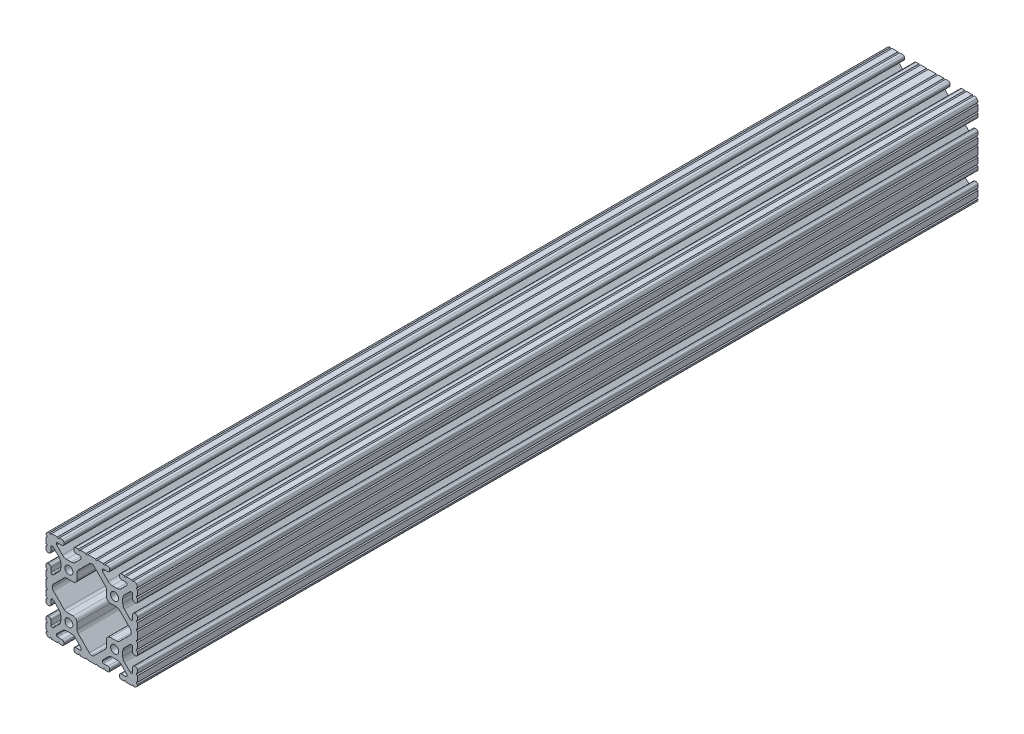
SolidWorks part; units mm, degrees
ref_plane "Front Plane" through (0, 0, 0) normal (0, 0, 1) x (1, 0, 0)
ref_plane "Top Plane" through (0, 0, 0) normal (0, 1, 0) x (1, 0, 0)
ref_plane "Right Plane" through (0, 0, 0) normal (1, 0, 0) x (0, 0, -1)
sketch "Sketch1" plane through (0, 0, 0) normal (0, 0, 1) x (1, 0, 0)
  line L0 (0, 38.1) -> (0, -38.1) construction
  line L1 (-38.1, -38.1) -> (38.1, -38.1) construction
  line L2 (-38.1, -38.1) -> (-38.1, 38.1) construction
  line L3 (-38.1, 38.1) -> (38.1, 38.1) construction
  line L4 (38.1, -38.1) -> (38.1, 38.1) construction
  line L5 (0, 38.1) -> (0, -38.1) construction
  line L6 (-38.1, 0) -> (38.1, 0) construction
  line L7 (-19.05, 19.05) -> (19.05, 19.05) construction
  line L8 (-19.05, 19.05) -> (-19.05, -19.05) construction
  line L9 (-19.05, -19.05) -> (19.05, -19.05) construction
  line L10 (19.05, 19.05) -> (19.05, -19.05) construction
  line L11 (-23.114, 38.1) -> (-23.114, -38.1) construction
  line L12 (-23.114, -38.1) -> (-14.986, 38.1) construction
  line L13 (-14.986, 38.1) -> (-14.986, -38.1) construction
  circle A0 centre (19.05, 19.05) radius 3.3274
  point P0 (0, 0)
  point P9 (0, 0)
  point P12 (-19.05, 0)
  line B0 (-11.3637, -22.8433) -> (-2.0515, -32.1555)
  line B1 (-12.2936, -15.4686) -> (-12.2936, -20.5983)
  line B2 (-20.769, -12.2936) -> (-15.4686, -12.2936)
  line B3 (-31.9021, -2.4756) -> (-23.0141, -11.3637)
  line B4 (-23.0141, 11.3637) -> (-31.9021, 2.4756)
  line B5 (-15.4686, 12.2936) -> (-20.769, 12.2936)
  line B6 (-12.2936, 20.5983) -> (-12.2936, 15.4686)
  line B7 (-2.0515, 32.1555) -> (-11.3637, 22.8433)
  line B8 (11.3637, 22.8433) -> (2.0515, 32.1555)
  line B9 (12.2936, 15.4686) -> (12.2936, 20.5983)
  line B10 (20.769, 12.2936) -> (15.4686, 12.2936)
  line B11 (31.9021, 2.4756) -> (23.0141, 11.3637)
  line B12 (23.0141, -11.3637) -> (31.9021, -2.4756)
  line B13 (15.4686, -12.2936) -> (20.769, -12.2936)
  line B14 (12.2936, -20.5983) -> (12.2936, -15.4686)
  line B15 (2.0515, -32.1555) -> (11.3637, -22.8433)
  line B16 (-4.7773, 38.1) -> (-9.6053, 38.1)
  line B17 (-11.1289, 38.1) -> (-13.4112, 38.1)
  line B18 (-14.986, 36.5252) -> (-14.986, 35.6108)
  line B19 (-13.4112, 34.036) -> (-9.652, 34.036)
  line B20 (-8.763, 33.147) -> (-8.763, 32.4935)
  line B21 (-9.0234, 31.8649) -> (-13.6907, 27.1976)
  line B22 (-17.0493, 25.8064) -> (-21.0507, 25.8064)
  line B23 (-24.4093, 27.1976) -> (-29.1002, 31.8885)
  line B24 (-29.337, 32.7207) -> (-29.337, 33.147)
  line B25 (-28.448, 34.036) -> (-24.6888, 34.036)
  line B26 (-23.114, 35.6108) -> (-23.114, 36.5252)
  line B27 (-24.6888, 38.1) -> (-27.0772, 38.1)
  line B28 (-28.6011, 38.1) -> (-33.4288, 38.1)
  line B29 (-38.1, 33.373) -> (-38.1, 28.5453)
  line B30 (-38.1, 27.0238) -> (-38.1, 24.6302)
  line B31 (-36.5252, 23.0554) -> (-35.6108, 23.0554)
  line B32 (-34.036, 24.6302) -> (-34.036, 28.448)
  line B33 (-33.147, 29.337) -> (-32.6643, 29.337)
  line B34 (-32.0357, 29.0766) -> (-27.1976, 24.2385)
  line B35 (-25.8064, 20.8799) -> (-25.8064, 17.2201)
  line B36 (-27.1976, 13.8615) -> (-31.9489, 9.1101)
  line B37 (-32.7869, 8.763) -> (-33.0603, 8.763)
  line B38 (-34.036, 9.7387) -> (-34.036, 13.4698)
  line B39 (-35.6108, 15.0446) -> (-36.5252, 15.0446)
  line B40 (-38.1, 13.4698) -> (-38.1, 11.075)
  line B41 (-38.1, 9.552) -> (-38.1, 4.7238)
  line B42 (-38.1, 3.2007) -> (-38.1, -3.2007)
  line B43 (-38.1, -4.7238) -> (-38.1, -9.552)
  line B44 (-38.1, -11.075) -> (-38.1, -13.4698)
  line B45 (-36.5252, -15.0446) -> (-35.6108, -15.0446)
  line B46 (-34.036, -13.4698) -> (-34.036, -9.7387)
  line B47 (-33.0603, -8.763) -> (-32.7869, -8.763)
  line B48 (-31.9489, -9.1101) -> (-27.1976, -13.8615)
  line B49 (-25.8064, -17.2201) -> (-25.8064, -20.8799)
  line B50 (-27.1976, -24.2385) -> (-32.0357, -29.0766)
  line B51 (-32.6643, -29.337) -> (-33.147, -29.337)
  line B52 (-34.036, -28.448) -> (-34.036, -24.6302)
  line B53 (-35.6108, -23.0554) -> (-36.5252, -23.0554)
  line B54 (-38.1, -24.6302) -> (-38.1, -27.0238)
  line B55 (-38.1, -28.5453) -> (-38.1, -33.373)
  line B56 (-33.4288, -38.1) -> (-28.6011, -38.1)
  line B57 (-27.0772, -38.1) -> (-24.6888, -38.1)
  line B58 (-23.114, -36.5252) -> (-23.114, -35.6108)
  line B59 (-24.6888, -34.036) -> (-28.448, -34.036)
  line B60 (-29.337, -33.147) -> (-29.337, -32.7207)
  line B61 (-29.1002, -31.8885) -> (-24.4093, -27.1976)
  line B62 (-21.0507, -25.8064) -> (-17.0493, -25.8064)
  line B63 (-13.6907, -27.1976) -> (-9.0234, -31.8649)
  line B64 (-8.763, -32.4935) -> (-8.763, -33.147)
  line B65 (-9.652, -34.036) -> (-13.4112, -34.036)
  line B66 (-14.986, -35.6108) -> (-14.986, -36.5252)
  line B67 (-13.4112, -38.1) -> (-11.1289, -38.1)
  line B68 (-9.6053, -38.1) -> (-4.7773, -38.1)
  line B69 (-3.2537, -38.1) -> (3.2537, -38.1)
  line B70 (4.7773, -38.1) -> (9.6053, -38.1)
  line B71 (11.1289, -38.1) -> (13.4112, -38.1)
  line B72 (14.986, -36.5252) -> (14.986, -35.6108)
  line B73 (13.4112, -34.036) -> (9.652, -34.036)
  line B74 (8.763, -33.147) -> (8.763, -32.4935)
  line B75 (9.0234, -31.8649) -> (13.6907, -27.1976)
  line B76 (17.0493, -25.8064) -> (21.0507, -25.8064)
  line B77 (24.4093, -27.1976) -> (29.1002, -31.8885)
  line B78 (29.337, -32.7207) -> (29.337, -33.147)
  line B79 (28.448, -34.036) -> (24.6888, -34.036)
  line B80 (23.114, -35.6108) -> (23.114, -36.5252)
  line B81 (24.6888, -38.1) -> (27.0772, -38.1)
  line B82 (28.6011, -38.1) -> (33.4288, -38.1)
  line B83 (38.1, -33.373) -> (38.1, -28.5453)
  line B84 (38.1, -27.0238) -> (38.1, -24.6302)
  line B85 (36.5252, -23.0554) -> (35.6108, -23.0554)
  line B86 (34.036, -24.6302) -> (34.036, -28.448)
  line B87 (33.147, -29.337) -> (32.6643, -29.337)
  line B88 (32.0357, -29.0766) -> (27.1976, -24.2385)
  line B89 (25.8064, -20.8799) -> (25.8064, -17.2201)
  line B90 (27.1976, -13.8615) -> (31.9489, -9.1101)
  line B91 (32.7869, -8.763) -> (33.0603, -8.763)
  line B92 (34.036, -9.7387) -> (34.036, -13.4698)
  line B93 (35.6108, -15.0446) -> (36.5252, -15.0446)
  line B94 (38.1, -13.4698) -> (38.1, -11.075)
  line B95 (38.1, -9.552) -> (38.1, -4.7238)
  line B96 (38.1, -3.2007) -> (38.1, 3.2007)
  line B97 (38.1, 4.7238) -> (38.1, 9.552)
  line B98 (38.1, 11.075) -> (38.1, 13.4698)
  line B99 (36.5252, 15.0446) -> (35.6108, 15.0446)
  line B100 (34.036, 13.4698) -> (34.036, 9.7387)
  line B101 (33.0603, 8.763) -> (32.7869, 8.763)
  line B102 (31.9489, 9.1101) -> (27.1976, 13.8615)
  line B103 (25.8064, 17.2201) -> (25.8064, 20.8799)
  line B104 (27.1976, 24.2385) -> (32.0357, 29.0766)
  line B105 (32.6643, 29.337) -> (33.147, 29.337)
  line B106 (34.036, 28.448) -> (34.036, 24.6302)
  line B107 (35.6108, 23.0554) -> (36.5252, 23.0554)
  line B108 (38.1, 24.6302) -> (38.1, 27.0238)
  line B109 (38.1, 28.5453) -> (38.1, 33.373)
  line B110 (33.4288, 38.1) -> (28.6011, 38.1)
  line B111 (27.0772, 38.1) -> (24.6888, 38.1)
  line B112 (23.114, 36.5252) -> (23.114, 35.6108)
  line B113 (24.6888, 34.036) -> (28.448, 34.036)
  line B114 (29.337, 33.147) -> (29.337, 32.7207)
  line B115 (29.1002, 31.8885) -> (24.4093, 27.1976)
  line B116 (21.0507, 25.8064) -> (17.0493, 25.8064)
  line B117 (13.6907, 27.1976) -> (9.0234, 31.8649)
  line B118 (8.763, 32.4935) -> (8.763, 33.147)
  line B119 (9.652, 34.036) -> (13.4112, 34.036)
  line B120 (14.986, 35.6108) -> (14.986, 36.5252)
  line B121 (13.4112, 38.1) -> (11.1289, 38.1)
  line B122 (9.6053, 38.1) -> (4.7773, 38.1)
  line B123 (3.2537, 38.1) -> (-3.2537, 38.1)
  circle B124 centre (-19.05, 19.05) radius 3.3274
  circle B125 centre (-19.05, -19.05) radius 3.3274
  circle B126 centre (19.05, -19.05) radius 3.3274
  circle B127 centre (19.05, 19.05) radius 3.3274
  arc B128 (0, -33.011) -> (2.0515, -32.1555) centre (-0.0139, -30.09) ccw
  arc B129 (-2.0515, -32.1555) -> (0, -33.011) centre (0.0139, -30.09) ccw
  arc B130 (-12.2936, -20.5983) -> (-11.3637, -22.8433) centre (-9.1186, -20.5983) ccw
  arc B131 (-12.2936, -15.4686) -> (-15.4686, -12.2936) centre (-15.4686, -15.4686) ccw
  arc B132 (-23.0141, -11.3637) -> (-20.769, -12.2936) centre (-20.769, -9.1186) ccw
  arc B133 (-32.7287, 0) -> (-31.9021, -2.4756) centre (-29.8367, -0.4102) ccw
  arc B134 (-31.9021, 2.4756) -> (-32.7287, 0) centre (-29.8367, 0.4102) ccw
  arc B135 (-20.769, 12.2936) -> (-23.0141, 11.3637) centre (-20.769, 9.1186) ccw
  arc B136 (-15.4686, 12.2936) -> (-12.2936, 15.4686) centre (-15.4686, 15.4686) ccw
  arc B137 (-11.3637, 22.8433) -> (-12.2936, 20.5983) centre (-9.1186, 20.5983) ccw
  arc B138 (0, 33.011) -> (-2.0515, 32.1555) centre (0.0139, 30.09) ccw
  arc B139 (2.0515, 32.1555) -> (0, 33.011) centre (-0.0139, 30.09) ccw
  arc B140 (12.2936, 20.5983) -> (11.3637, 22.8433) centre (9.1186, 20.5983) ccw
  arc B141 (12.2936, 15.4686) -> (15.4686, 12.2936) centre (15.4686, 15.4686) ccw
  arc B142 (23.0141, 11.3637) -> (20.769, 12.2936) centre (20.769, 9.1186) ccw
  arc B143 (32.7287, 0) -> (31.9021, 2.4756) centre (29.8367, 0.4102) ccw
  arc B144 (31.9021, -2.4756) -> (32.7287, 0) centre (29.8367, -0.4102) ccw
  arc B145 (20.769, -12.2936) -> (23.0141, -11.3637) centre (20.769, -9.1186) ccw
  arc B146 (15.4686, -12.2936) -> (12.2936, -15.4686) centre (15.4686, -15.4686) ccw
  arc B147 (11.3637, -22.8433) -> (12.2936, -20.5983) centre (9.1186, -20.5983) ccw
  arc B148 (-4.7773, 38.1) -> (-3.2537, 38.1) centre (-4.0155, 38.0824) ccw
  arc B149 (-11.1289, 38.1) -> (-9.6053, 38.1) centre (-10.3671, 38.0824) ccw
  arc B150 (-13.4112, 38.1) -> (-14.986, 36.5252) centre (-13.4112, 36.5252) ccw
  arc B151 (-14.986, 35.6108) -> (-13.4112, 34.036) centre (-13.4112, 35.6108) ccw
  arc B152 (-8.763, 33.147) -> (-9.652, 34.036) centre (-9.652, 33.147) ccw
  arc B153 (-9.0234, 31.8649) -> (-8.763, 32.4935) centre (-9.652, 32.4935) ccw
  arc B154 (-17.0493, 25.8064) -> (-13.6907, 27.1976) centre (-17.0493, 30.5562) ccw
  arc B155 (-24.4093, 27.1976) -> (-21.0507, 25.8064) centre (-21.0507, 30.5562) ccw
  arc B156 (-29.337, 32.7207) -> (-29.1002, 31.8885) centre (-28.4716, 32.5172) ccw
  arc B157 (-28.448, 34.036) -> (-29.337, 33.147) centre (-28.448, 33.147) ccw
  arc B158 (-24.6888, 34.036) -> (-23.114, 35.6108) centre (-24.6888, 35.6108) ccw
  arc B159 (-23.114, 36.5252) -> (-24.6888, 38.1) centre (-24.6888, 36.5252) ccw
  arc B160 (-28.6011, 38.1) -> (-27.0772, 38.1) centre (-27.8392, 38.0824) ccw
  arc B161 (-34.9527, 38.1) -> (-33.4288, 38.1) centre (-34.1907, 38.0824) ccw
  arc B162 (-34.9527, 38.1) -> (-37.0861, 37.1826) centre (-34.8521, 34.9266) ccw
  arc B163 (-37.0861, 37.1826) -> (-38.1, 34.8455) centre (-34.925, 34.8566) ccw
  arc B164 (-38.1, 33.373) -> (-38.1, 34.8455) centre (-37.9035, 34.1092) ccw
  arc B165 (-38.1, 27.0238) -> (-38.1, 28.5453) centre (-37.9035, 27.7845) ccw
  arc B166 (-38.1, 24.6302) -> (-36.5252, 23.0554) centre (-36.5252, 24.6302) ccw
  arc B167 (-35.6108, 23.0554) -> (-34.036, 24.6302) centre (-35.6108, 24.6302) ccw
  arc B168 (-33.147, 29.337) -> (-34.036, 28.448) centre (-33.147, 28.448) ccw
  arc B169 (-32.0357, 29.0766) -> (-32.6643, 29.337) centre (-32.6643, 28.448) ccw
  arc B170 (-25.8064, 20.8799) -> (-27.1976, 24.2385) centre (-30.5562, 20.8799) ccw
  arc B171 (-27.1976, 13.8615) -> (-25.8064, 17.2201) centre (-30.5562, 17.2201) ccw
  arc B172 (-32.7869, 8.763) -> (-31.9489, 9.1101) centre (-32.7869, 9.9481) ccw
  arc B173 (-34.036, 9.7387) -> (-33.0603, 8.763) centre (-33.0603, 9.7387) ccw
  arc B174 (-34.036, 13.4698) -> (-35.6108, 15.0446) centre (-35.6108, 13.4698) ccw
  arc B175 (-36.5252, 15.0446) -> (-38.1, 13.4698) centre (-36.5252, 13.4698) ccw
  arc B176 (-38.1, 9.552) -> (-38.1, 11.075) centre (-37.9035, 10.3135) ccw
  arc B177 (-38.1, 3.2007) -> (-38.1, 4.7238) centre (-37.9035, 3.9622) ccw
  arc B178 (-38.1, -4.7238) -> (-38.1, -3.2007) centre (-37.9035, -3.9622) ccw
  arc B179 (-38.1, -11.075) -> (-38.1, -9.552) centre (-37.9035, -10.3135) ccw
  arc B180 (-38.1, -13.4698) -> (-36.5252, -15.0446) centre (-36.5252, -13.4698) ccw
  arc B181 (-35.6108, -15.0446) -> (-34.036, -13.4698) centre (-35.6108, -13.4698) ccw
  arc B182 (-33.0603, -8.763) -> (-34.036, -9.7387) centre (-33.0603, -9.7387) ccw
  arc B183 (-31.9489, -9.1101) -> (-32.7869, -8.763) centre (-32.7869, -9.9481) ccw
  arc B184 (-25.8064, -17.2201) -> (-27.1976, -13.8615) centre (-30.5562, -17.2201) ccw
  arc B185 (-27.1976, -24.2385) -> (-25.8064, -20.8799) centre (-30.5562, -20.8799) ccw
  arc B186 (-32.6643, -29.337) -> (-32.0357, -29.0766) centre (-32.6643, -28.448) ccw
  arc B187 (-34.036, -28.448) -> (-33.147, -29.337) centre (-33.147, -28.448) ccw
  arc B188 (-34.036, -24.6302) -> (-35.6108, -23.0554) centre (-35.6108, -24.6302) ccw
  arc B189 (-36.5252, -23.0554) -> (-38.1, -24.6302) centre (-36.5252, -24.6302) ccw
  arc B190 (-38.1, -28.5453) -> (-38.1, -27.0238) centre (-37.9035, -27.7845) ccw
  arc B191 (-38.1, -34.8455) -> (-38.1, -33.373) centre (-37.9035, -34.1092) ccw
  arc B192 (-38.1, -34.8455) -> (-37.0861, -37.1826) centre (-34.925, -34.8566) ccw
  arc B193 (-37.0861, -37.1826) -> (-34.9527, -38.1) centre (-34.8521, -34.9266) ccw
  arc B194 (-33.4288, -38.1) -> (-34.9527, -38.1) centre (-34.1907, -38.0824) ccw
  arc B195 (-27.0772, -38.1) -> (-28.6011, -38.1) centre (-27.8392, -38.0824) ccw
  arc B196 (-24.6888, -38.1) -> (-23.114, -36.5252) centre (-24.6888, -36.5252) ccw
  arc B197 (-23.114, -35.6108) -> (-24.6888, -34.036) centre (-24.6888, -35.6108) ccw
  arc B198 (-29.337, -33.147) -> (-28.448, -34.036) centre (-28.448, -33.147) ccw
  arc B199 (-29.1002, -31.8885) -> (-29.337, -32.7207) centre (-28.4716, -32.5172) ccw
  arc B200 (-21.0507, -25.8064) -> (-24.4093, -27.1976) centre (-21.0507, -30.5562) ccw
  arc B201 (-13.6907, -27.1976) -> (-17.0493, -25.8064) centre (-17.0493, -30.5562) ccw
  arc B202 (-8.763, -32.4935) -> (-9.0234, -31.8649) centre (-9.652, -32.4935) ccw
  arc B203 (-9.652, -34.036) -> (-8.763, -33.147) centre (-9.652, -33.147) ccw
  arc B204 (-13.4112, -34.036) -> (-14.986, -35.6108) centre (-13.4112, -35.6108) ccw
  arc B205 (-14.986, -36.5252) -> (-13.4112, -38.1) centre (-13.4112, -36.5252) ccw
  arc B206 (-9.6053, -38.1) -> (-11.1289, -38.1) centre (-10.3671, -38.0824) ccw
  arc B207 (-3.2537, -38.1) -> (-4.7773, -38.1) centre (-4.0155, -38.0824) ccw
  arc B208 (4.7773, -38.1) -> (3.2537, -38.1) centre (4.0155, -38.0824) ccw
  arc B209 (11.1289, -38.1) -> (9.6053, -38.1) centre (10.3671, -38.0824) ccw
  arc B210 (13.4112, -38.1) -> (14.986, -36.5252) centre (13.4112, -36.5252) ccw
  arc B211 (14.986, -35.6108) -> (13.4112, -34.036) centre (13.4112, -35.6108) ccw
  arc B212 (8.763, -33.147) -> (9.652, -34.036) centre (9.652, -33.147) ccw
  arc B213 (9.0234, -31.8649) -> (8.763, -32.4935) centre (9.652, -32.4935) ccw
  arc B214 (17.0493, -25.8064) -> (13.6907, -27.1976) centre (17.0493, -30.5562) ccw
  arc B215 (24.4093, -27.1976) -> (21.0507, -25.8064) centre (21.0507, -30.5562) ccw
  arc B216 (29.337, -32.7207) -> (29.1002, -31.8885) centre (28.4716, -32.5172) ccw
  arc B217 (28.448, -34.036) -> (29.337, -33.147) centre (28.448, -33.147) ccw
  arc B218 (24.6888, -34.036) -> (23.114, -35.6108) centre (24.6888, -35.6108) ccw
  arc B219 (23.114, -36.5252) -> (24.6888, -38.1) centre (24.6888, -36.5252) ccw
  arc B220 (28.6011, -38.1) -> (27.0772, -38.1) centre (27.8392, -38.0824) ccw
  arc B221 (34.9527, -38.1) -> (33.4288, -38.1) centre (34.1907, -38.0824) ccw
  arc B222 (34.9527, -38.1) -> (37.0861, -37.1826) centre (34.8521, -34.9266) ccw
  arc B223 (37.0861, -37.1826) -> (38.1, -34.8455) centre (34.925, -34.8566) ccw
  arc B224 (38.1, -33.373) -> (38.1, -34.8455) centre (37.9035, -34.1092) ccw
  arc B225 (38.1, -27.0238) -> (38.1, -28.5453) centre (37.9035, -27.7845) ccw
  arc B226 (38.1, -24.6302) -> (36.5252, -23.0554) centre (36.5252, -24.6302) ccw
  arc B227 (35.6108, -23.0554) -> (34.036, -24.6302) centre (35.6108, -24.6302) ccw
  arc B228 (33.147, -29.337) -> (34.036, -28.448) centre (33.147, -28.448) ccw
  arc B229 (32.0357, -29.0766) -> (32.6643, -29.337) centre (32.6643, -28.448) ccw
  arc B230 (25.8064, -20.8799) -> (27.1976, -24.2385) centre (30.5562, -20.8799) ccw
  arc B231 (27.1976, -13.8615) -> (25.8064, -17.2201) centre (30.5562, -17.2201) ccw
  arc B232 (32.7869, -8.763) -> (31.9489, -9.1101) centre (32.7869, -9.9481) ccw
  arc B233 (34.036, -9.7387) -> (33.0603, -8.763) centre (33.0603, -9.7387) ccw
  arc B234 (34.036, -13.4698) -> (35.6108, -15.0446) centre (35.6108, -13.4698) ccw
  arc B235 (36.5252, -15.0446) -> (38.1, -13.4698) centre (36.5252, -13.4698) ccw
  arc B236 (38.1, -9.552) -> (38.1, -11.075) centre (37.9035, -10.3135) ccw
  arc B237 (38.1, -3.2007) -> (38.1, -4.7238) centre (37.9035, -3.9622) ccw
  arc B238 (38.1, 4.7238) -> (38.1, 3.2007) centre (37.9035, 3.9622) ccw
  arc B239 (38.1, 11.075) -> (38.1, 9.552) centre (37.9035, 10.3135) ccw
  arc B240 (38.1, 13.4698) -> (36.5252, 15.0446) centre (36.5252, 13.4698) ccw
  arc B241 (35.6108, 15.0446) -> (34.036, 13.4698) centre (35.6108, 13.4698) ccw
  arc B242 (33.0603, 8.763) -> (34.036, 9.7387) centre (33.0603, 9.7387) ccw
  arc B243 (31.9489, 9.1101) -> (32.7869, 8.763) centre (32.7869, 9.9481) ccw
  arc B244 (25.8064, 17.2201) -> (27.1976, 13.8615) centre (30.5562, 17.2201) ccw
  arc B245 (27.1976, 24.2385) -> (25.8064, 20.8799) centre (30.5562, 20.8799) ccw
  arc B246 (32.6643, 29.337) -> (32.0357, 29.0766) centre (32.6643, 28.448) ccw
  arc B247 (34.036, 28.448) -> (33.147, 29.337) centre (33.147, 28.448) ccw
  arc B248 (34.036, 24.6302) -> (35.6108, 23.0554) centre (35.6108, 24.6302) ccw
  arc B249 (36.5252, 23.0554) -> (38.1, 24.6302) centre (36.5252, 24.6302) ccw
  arc B250 (38.1, 28.5453) -> (38.1, 27.0238) centre (37.9035, 27.7845) ccw
  arc B251 (38.1, 34.8455) -> (38.1, 33.373) centre (37.9035, 34.1092) ccw
  arc B252 (38.1, 34.8455) -> (37.0861, 37.1826) centre (34.925, 34.8566) ccw
  arc B253 (37.0861, 37.1826) -> (34.9527, 38.1) centre (34.8521, 34.9266) ccw
  arc B254 (33.4288, 38.1) -> (34.9527, 38.1) centre (34.1907, 38.0824) ccw
  arc B255 (27.0772, 38.1) -> (28.6011, 38.1) centre (27.8392, 38.0824) ccw
  arc B256 (24.6888, 38.1) -> (23.114, 36.5252) centre (24.6888, 36.5252) ccw
  arc B257 (23.114, 35.6108) -> (24.6888, 34.036) centre (24.6888, 35.6108) ccw
  arc B258 (29.337, 33.147) -> (28.448, 34.036) centre (28.448, 33.147) ccw
  arc B259 (29.1002, 31.8885) -> (29.337, 32.7207) centre (28.4716, 32.5172) ccw
  arc B260 (21.0507, 25.8064) -> (24.4093, 27.1976) centre (21.0507, 30.5562) ccw
  arc B261 (13.6907, 27.1976) -> (17.0493, 25.8064) centre (17.0493, 30.5562) ccw
  arc B262 (8.763, 32.4935) -> (9.0234, 31.8649) centre (9.652, 32.4935) ccw
  arc B263 (9.652, 34.036) -> (8.763, 33.147) centre (9.652, 33.147) ccw
  arc B264 (13.4112, 34.036) -> (14.986, 35.6108) centre (13.4112, 35.6108) ccw
  arc B265 (14.986, 36.5252) -> (13.4112, 38.1) centre (13.4112, 36.5252) ccw
  arc B266 (9.6053, 38.1) -> (11.1289, 38.1) centre (10.3671, 38.0824) ccw
  arc B267 (3.2537, 38.1) -> (4.7773, 38.1) centre (4.0155, 38.0824) ccw
  dimension "Center Hole Diameter" = 6.6548
  dimension "Rail Width" = 76.2
  dimension "Rail Height" = 76.2
  dimension "T-Slot Width" = 8.128
sketch_block_instance "Block1-1"
sketch_block "Block1"
sketch "Sketch2" plane through (0, 0, 0) normal (1, 0, 0) x (0, 0, -1)
  line L0 (-350, 0) -> (350, 0) construction
  line L1 (-350, 38.1) -> (-350, -38.1) construction
  line L2 (-350, -38.1) -> (350, -38.1) construction
  line L3 (350, -38.1) -> (350, 38.1) construction
  line L4 (-248.4, 0) -> (-248.4, 38.1) construction
  line L5 (-248.4, 38.1) -> (248.4, 38.1) construction
  line L6 (248.4, 38.1) -> (248.4, 0) construction
  point P5 (248.4, 0)
  point P10 (-248.4, 0)
  dimension "D1" = 101.6
  dimension "Length" = 700
  dimension "D2" = 101.6
sketch "Sketch3" plane through (0, 0, 0) normal (0, 0, 1) x (1, 0, 0)
  line L0 (-11.3637, -22.8433) -> (-2.0515, -32.1555) construction
  line L1 (-12.2936, -15.4686) -> (-12.2936, -20.5983) construction
  line L2 (-20.769, -12.2936) -> (-15.4686, -12.2936) construction
  line L3 (-31.9021, -2.4756) -> (-23.0141, -11.3637) construction
  line L4 (-23.0141, 11.3637) -> (-31.9021, 2.4756) construction
  line L5 (-15.4686, 12.2936) -> (-20.769, 12.2936) construction
  line L6 (-12.2936, 20.5983) -> (-12.2936, 15.4686) construction
  line L7 (-2.0515, 32.1555) -> (-11.3637, 22.8433) construction
  line L8 (11.3637, 22.8433) -> (2.0515, 32.1555) construction
  line L9 (12.2936, 15.4686) -> (12.2936, 20.5983) construction
  line L10 (20.769, 12.2936) -> (15.4686, 12.2936) construction
  line L11 (31.9021, 2.4756) -> (23.0141, 11.3637) construction
  line L12 (23.0141, -11.3637) -> (31.9021, -2.4756) construction
  line L13 (15.4686, -12.2936) -> (20.769, -12.2936) construction
  line L14 (12.2936, -20.5983) -> (12.2936, -15.4686) construction
  line L15 (2.0515, -32.1555) -> (11.3637, -22.8433) construction
  line L16 (34.036, 28.448) -> (34.036, 24.6302) construction
  line L17 (35.6108, 23.0554) -> (36.5252, 23.0554) construction
  line L18 (38.1, 24.6302) -> (38.1, 27.0238) construction
  line L19 (38.1, 28.5453) -> (38.1, 33.373) construction
  line L20 (33.4288, 38.1) -> (28.6011, 38.1) construction
  line L21 (27.0772, 38.1) -> (24.6888, 38.1) construction
  line L22 (23.114, 36.5252) -> (23.114, 35.6108) construction
  line L23 (24.6888, 34.036) -> (28.448, 34.036) construction
  line L24 (29.337, 33.147) -> (29.337, 32.7207) construction
  line L25 (29.1002, 31.8885) -> (24.4093, 27.1976) construction
  line L26 (21.0507, 25.8064) -> (17.0493, 25.8064) construction
  line L27 (13.6907, 27.1976) -> (9.0234, 31.8649) construction
  line L28 (8.763, 32.4935) -> (8.763, 33.147) construction
  line L29 (9.652, 34.036) -> (13.4112, 34.036) construction
  line L30 (14.986, 35.6108) -> (14.986, 36.5252) construction
  line L31 (13.4112, 38.1) -> (11.1289, 38.1) construction
  line L32 (9.6053, 38.1) -> (4.7773, 38.1) construction
  line L33 (3.2537, 38.1) -> (-3.2537, 38.1) construction
  line L34 (-4.7773, 38.1) -> (-9.6053, 38.1) construction
  line L35 (-11.1289, 38.1) -> (-13.4112, 38.1) construction
  line L36 (-14.986, 36.5252) -> (-14.986, 35.6108) construction
  line L37 (-13.4112, 34.036) -> (-9.652, 34.036) construction
  line L38 (-8.763, 33.147) -> (-8.763, 32.4935) construction
  line L39 (-9.0234, 31.8649) -> (-13.6907, 27.1976) construction
  line L40 (-17.0493, 25.8064) -> (-21.0507, 25.8064) construction
  line L41 (-24.4093, 27.1976) -> (-29.1002, 31.8885) construction
  line L42 (-29.337, 32.7207) -> (-29.337, 33.147) construction
  line L43 (-28.448, 34.036) -> (-24.6888, 34.036) construction
  line L44 (-23.114, 35.6108) -> (-23.114, 36.5252) construction
  line L45 (-24.6888, 38.1) -> (-27.0772, 38.1) construction
  line L46 (-28.6011, 38.1) -> (-33.4288, 38.1) construction
  line L47 (-38.1, 33.373) -> (-38.1, 28.5453) construction
  line L48 (-38.1, 27.0238) -> (-38.1, 24.6302) construction
  line L49 (-36.5252, 23.0554) -> (-35.6108, 23.0554) construction
  line L50 (-34.036, 24.6302) -> (-34.036, 28.448) construction
  line L51 (-33.147, 29.337) -> (-32.6643, 29.337) construction
  line L52 (-32.0357, 29.0766) -> (-27.1976, 24.2385) construction
  line L53 (-25.8064, 20.8799) -> (-25.8064, 17.2201) construction
  line L54 (-27.1976, 13.8615) -> (-31.9489, 9.1101) construction
  line L55 (-32.7869, 8.763) -> (-33.0603, 8.763) construction
  line L56 (-34.036, 9.7387) -> (-34.036, 13.4698) construction
  line L57 (-35.6108, 15.0446) -> (-36.5252, 15.0446) construction
  line L58 (-38.1, 13.4698) -> (-38.1, 11.075) construction
  line L59 (-38.1, 9.552) -> (-38.1, 4.7238) construction
  line L60 (-38.1, 3.2007) -> (-38.1, -3.2007) construction
  line L61 (-38.1, -4.7238) -> (-38.1, -9.552) construction
  line L62 (-38.1, -11.075) -> (-38.1, -13.4698) construction
  line L63 (-36.5252, -15.0446) -> (-35.6108, -15.0446) construction
  line L64 (-34.036, -13.4698) -> (-34.036, -9.7387) construction
  line L65 (-33.0603, -8.763) -> (-32.7869, -8.763) construction
  line L66 (-31.9489, -9.1101) -> (-27.1976, -13.8615) construction
  line L67 (-25.8064, -17.2201) -> (-25.8064, -20.8799) construction
  line L68 (-27.1976, -24.2385) -> (-32.0357, -29.0766) construction
  line L69 (-32.6643, -29.337) -> (-33.147, -29.337) construction
  line L70 (-34.036, -28.448) -> (-34.036, -24.6302) construction
  line L71 (-35.6108, -23.0554) -> (-36.5252, -23.0554) construction
  line L72 (-38.1, -24.6302) -> (-38.1, -27.0238) construction
  line L73 (-38.1, -28.5453) -> (-38.1, -33.373) construction
  line L74 (-33.4288, -38.1) -> (-28.6011, -38.1) construction
  line L75 (-27.0772, -38.1) -> (-24.6888, -38.1) construction
  line L76 (-23.114, -36.5252) -> (-23.114, -35.6108) construction
  line L77 (-24.6888, -34.036) -> (-28.448, -34.036) construction
  line L78 (-29.337, -33.147) -> (-29.337, -32.7207) construction
  line L79 (-29.1002, -31.8885) -> (-24.4093, -27.1976) construction
  line L80 (-21.0507, -25.8064) -> (-17.0493, -25.8064) construction
  line L81 (-13.6907, -27.1976) -> (-9.0234, -31.8649) construction
  line L82 (-8.763, -32.4935) -> (-8.763, -33.147) construction
  line L83 (-9.652, -34.036) -> (-13.4112, -34.036) construction
  line L84 (-14.986, -35.6108) -> (-14.986, -36.5252) construction
  line L85 (-13.4112, -38.1) -> (-11.1289, -38.1) construction
  line L86 (-9.6053, -38.1) -> (-4.7773, -38.1) construction
  line L87 (-3.2537, -38.1) -> (3.2537, -38.1) construction
  line L88 (4.7773, -38.1) -> (9.6053, -38.1) construction
  line L89 (11.1289, -38.1) -> (13.4112, -38.1) construction
  line L90 (14.986, -36.5252) -> (14.986, -35.6108) construction
  line L91 (13.4112, -34.036) -> (9.652, -34.036) construction
  line L92 (8.763, -33.147) -> (8.763, -32.4935) construction
  line L93 (9.0234, -31.8649) -> (13.6907, -27.1976) construction
  line L94 (17.0493, -25.8064) -> (21.0507, -25.8064) construction
  line L95 (24.4093, -27.1976) -> (29.1002, -31.8885) construction
  line L96 (29.337, -32.7207) -> (29.337, -33.147) construction
  line L97 (28.448, -34.036) -> (24.6888, -34.036) construction
  line L98 (23.114, -35.6108) -> (23.114, -36.5252) construction
  line L99 (24.6888, -38.1) -> (27.0772, -38.1) construction
  line L100 (28.6011, -38.1) -> (33.4288, -38.1) construction
  line L101 (38.1, -33.373) -> (38.1, -28.5453) construction
  line L102 (38.1, -27.0238) -> (38.1, -24.6302) construction
  line L103 (36.5252, -23.0554) -> (35.6108, -23.0554) construction
  line L104 (34.036, -24.6302) -> (34.036, -28.448) construction
  line L105 (33.147, -29.337) -> (32.6643, -29.337) construction
  line L106 (32.0357, -29.0766) -> (27.1976, -24.2385) construction
  line L107 (25.8064, -20.8799) -> (25.8064, -17.2201) construction
  line L108 (27.1976, -13.8615) -> (31.9489, -9.1101) construction
  line L109 (32.7869, -8.763) -> (33.0603, -8.763) construction
  line L110 (34.036, -9.7387) -> (34.036, -13.4698) construction
  line L111 (35.6108, -15.0446) -> (36.5252, -15.0446) construction
  line L112 (38.1, -13.4698) -> (38.1, -11.075) construction
  line L113 (38.1, -9.552) -> (38.1, -4.7238) construction
  line L114 (38.1, -3.2007) -> (38.1, 3.2007) construction
  line L115 (38.1, 4.7238) -> (38.1, 9.552) construction
  line L116 (38.1, 11.075) -> (38.1, 13.4698) construction
  line L117 (36.5252, 15.0446) -> (35.6108, 15.0446) construction
  line L118 (34.036, 13.4698) -> (34.036, 9.7387) construction
  line L119 (33.0603, 8.763) -> (32.7869, 8.763) construction
  line L120 (31.9489, 9.1101) -> (27.1976, 13.8615) construction
  line L121 (25.8064, 17.2201) -> (25.8064, 20.8799) construction
  line L122 (27.1976, 24.2385) -> (32.0357, 29.0766) construction
  line L123 (32.6643, 29.337) -> (33.147, 29.337) construction
  line L124 (-11.3637, -22.8433) -> (-2.0515, -32.1555)
  line L125 (-12.2936, -15.4686) -> (-12.2936, -20.5983)
  line L126 (-20.769, -12.2936) -> (-15.4686, -12.2936)
  line L127 (-31.9021, -2.4756) -> (-23.0141, -11.3637)
  line L128 (-23.0141, 11.3637) -> (-31.9021, 2.4756)
  line L129 (-15.4686, 12.2936) -> (-20.769, 12.2936)
  line L130 (-12.2936, 20.5983) -> (-12.2936, 15.4686)
  line L131 (-2.0515, 32.1555) -> (-11.3637, 22.8433)
  line L132 (11.3637, 22.8433) -> (2.0515, 32.1555)
  line L133 (12.2936, 15.4686) -> (12.2936, 20.5983)
  line L134 (20.769, 12.2936) -> (15.4686, 12.2936)
  line L135 (31.9021, 2.4756) -> (23.0141, 11.3637)
  line L136 (23.0141, -11.3637) -> (31.9021, -2.4756)
  line L137 (15.4686, -12.2936) -> (20.769, -12.2936)
  line L138 (12.2936, -20.5983) -> (12.2936, -15.4686)
  line L139 (2.0515, -32.1555) -> (11.3637, -22.8433)
  line L140 (34.036, 28.448) -> (34.036, 24.6302)
  line L141 (35.6108, 23.0554) -> (36.5252, 23.0554)
  line L142 (38.1, 24.6302) -> (38.1, 27.0238)
  line L143 (38.1, 28.5453) -> (38.1, 33.373)
  line L144 (33.4288, 38.1) -> (28.6011, 38.1)
  line L145 (27.0772, 38.1) -> (24.6888, 38.1)
  line L146 (23.114, 36.5252) -> (23.114, 35.6108)
  line L147 (24.6888, 34.036) -> (28.448, 34.036)
  line L148 (29.337, 33.147) -> (29.337, 32.7207)
  line L149 (29.1002, 31.8885) -> (24.4093, 27.1976)
  line L150 (21.0507, 25.8064) -> (17.0493, 25.8064)
  line L151 (13.6907, 27.1976) -> (9.0234, 31.8649)
  line L152 (8.763, 32.4935) -> (8.763, 33.147)
  line L153 (9.652, 34.036) -> (13.4112, 34.036)
  line L154 (14.986, 35.6108) -> (14.986, 36.5252)
  line L155 (13.4112, 38.1) -> (11.1289, 38.1)
  line L156 (9.6053, 38.1) -> (4.7773, 38.1)
  line L157 (3.2537, 38.1) -> (-3.2537, 38.1)
  line L158 (-4.7773, 38.1) -> (-9.6053, 38.1)
  line L159 (-11.1289, 38.1) -> (-13.4112, 38.1)
  line L160 (-14.986, 36.5252) -> (-14.986, 35.6108)
  line L161 (-13.4112, 34.036) -> (-9.652, 34.036)
  line L162 (-8.763, 33.147) -> (-8.763, 32.4935)
  line L163 (-9.0234, 31.8649) -> (-13.6907, 27.1976)
  line L164 (-17.0493, 25.8064) -> (-21.0507, 25.8064)
  line L165 (-24.4093, 27.1976) -> (-29.1002, 31.8885)
  line L166 (-29.337, 32.7207) -> (-29.337, 33.147)
  line L167 (-28.448, 34.036) -> (-24.6888, 34.036)
  line L168 (-23.114, 35.6108) -> (-23.114, 36.5252)
  line L169 (-24.6888, 38.1) -> (-27.0772, 38.1)
  line L170 (-28.6011, 38.1) -> (-33.4288, 38.1)
  line L171 (-38.1, 33.373) -> (-38.1, 28.5453)
  line L172 (-38.1, 27.0238) -> (-38.1, 24.6302)
  line L173 (-36.5252, 23.0554) -> (-35.6108, 23.0554)
  line L174 (-34.036, 24.6302) -> (-34.036, 28.448)
  line L175 (-33.147, 29.337) -> (-32.6643, 29.337)
  line L176 (-32.0357, 29.0766) -> (-27.1976, 24.2385)
  line L177 (-25.8064, 20.8799) -> (-25.8064, 17.2201)
  line L178 (-27.1976, 13.8615) -> (-31.9489, 9.1101)
  line L179 (-32.7869, 8.763) -> (-33.0603, 8.763)
  line L180 (-34.036, 9.7387) -> (-34.036, 13.4698)
  line L181 (-35.6108, 15.0446) -> (-36.5252, 15.0446)
  line L182 (-38.1, 13.4698) -> (-38.1, 11.075)
  line L183 (-38.1, 9.552) -> (-38.1, 4.7238)
  line L184 (-38.1, 3.2007) -> (-38.1, -3.2007)
  line L185 (-38.1, -4.7238) -> (-38.1, -9.552)
  line L186 (-38.1, -11.075) -> (-38.1, -13.4698)
  line L187 (-36.5252, -15.0446) -> (-35.6108, -15.0446)
  line L188 (-34.036, -13.4698) -> (-34.036, -9.7387)
  line L189 (-33.0603, -8.763) -> (-32.7869, -8.763)
  line L190 (-31.9489, -9.1101) -> (-27.1976, -13.8615)
  line L191 (-25.8064, -17.2201) -> (-25.8064, -20.8799)
  line L192 (-27.1976, -24.2385) -> (-32.0357, -29.0766)
  line L193 (-32.6643, -29.337) -> (-33.147, -29.337)
  line L194 (-34.036, -28.448) -> (-34.036, -24.6302)
  line L195 (-35.6108, -23.0554) -> (-36.5252, -23.0554)
  line L196 (-38.1, -24.6302) -> (-38.1, -27.0238)
  line L197 (-38.1, -28.5453) -> (-38.1, -33.373)
  line L198 (-33.4288, -38.1) -> (-28.6011, -38.1)
  line L199 (-27.0772, -38.1) -> (-24.6888, -38.1)
  line L200 (-23.114, -36.5252) -> (-23.114, -35.6108)
  line L201 (-24.6888, -34.036) -> (-28.448, -34.036)
  line L202 (-29.337, -33.147) -> (-29.337, -32.7207)
  line L203 (-29.1002, -31.8885) -> (-24.4093, -27.1976)
  line L204 (-21.0507, -25.8064) -> (-17.0493, -25.8064)
  line L205 (-13.6907, -27.1976) -> (-9.0234, -31.8649)
  line L206 (-8.763, -32.4935) -> (-8.763, -33.147)
  line L207 (-9.652, -34.036) -> (-13.4112, -34.036)
  line L208 (-14.986, -35.6108) -> (-14.986, -36.5252)
  line L209 (-13.4112, -38.1) -> (-11.1289, -38.1)
  line L210 (-9.6053, -38.1) -> (-4.7773, -38.1)
  line L211 (-3.2537, -38.1) -> (3.2537, -38.1)
  line L212 (4.7773, -38.1) -> (9.6053, -38.1)
  line L213 (11.1289, -38.1) -> (13.4112, -38.1)
  line L214 (14.986, -36.5252) -> (14.986, -35.6108)
  line L215 (13.4112, -34.036) -> (9.652, -34.036)
  line L216 (8.763, -33.147) -> (8.763, -32.4935)
  line L217 (9.0234, -31.8649) -> (13.6907, -27.1976)
  line L218 (17.0493, -25.8064) -> (21.0507, -25.8064)
  line L219 (24.4093, -27.1976) -> (29.1002, -31.8885)
  line L220 (29.337, -32.7207) -> (29.337, -33.147)
  line L221 (28.448, -34.036) -> (24.6888, -34.036)
  line L222 (23.114, -35.6108) -> (23.114, -36.5252)
  line L223 (24.6888, -38.1) -> (27.0772, -38.1)
  line L224 (28.6011, -38.1) -> (33.4288, -38.1)
  line L225 (38.1, -33.373) -> (38.1, -28.5453)
  line L226 (38.1, -27.0238) -> (38.1, -24.6302)
  line L227 (36.5252, -23.0554) -> (35.6108, -23.0554)
  line L228 (34.036, -24.6302) -> (34.036, -28.448)
  line L229 (33.147, -29.337) -> (32.6643, -29.337)
  line L230 (32.0357, -29.0766) -> (27.1976, -24.2385)
  line L231 (25.8064, -20.8799) -> (25.8064, -17.2201)
  line L232 (27.1976, -13.8615) -> (31.9489, -9.1101)
  line L233 (32.7869, -8.763) -> (33.0603, -8.763)
  line L234 (34.036, -9.7387) -> (34.036, -13.4698)
  line L235 (35.6108, -15.0446) -> (36.5252, -15.0446)
  line L236 (38.1, -13.4698) -> (38.1, -11.075)
  line L237 (38.1, -9.552) -> (38.1, -4.7238)
  line L238 (38.1, -3.2007) -> (38.1, 3.2007)
  line L239 (38.1, 4.7238) -> (38.1, 9.552)
  line L240 (38.1, 11.075) -> (38.1, 13.4698)
  line L241 (36.5252, 15.0446) -> (35.6108, 15.0446)
  line L242 (34.036, 13.4698) -> (34.036, 9.7387)
  line L243 (33.0603, 8.763) -> (32.7869, 8.763)
  line L244 (31.9489, 9.1101) -> (27.1976, 13.8615)
  line L245 (25.8064, 17.2201) -> (25.8064, 20.8799)
  line L246 (27.1976, 24.2385) -> (32.0357, 29.0766)
  line L247 (32.6643, 29.337) -> (33.147, 29.337)
  arc A0 (-2.0515, -32.1555) -> (0, -33.011) centre (0.0139, -30.09) ccw construction
  circle A1 centre (19.05, 19.05) radius 3.3274
  circle A2 centre (19.05, 19.05) radius 3.3274
  arc A3 (-12.2936, -20.5983) -> (-11.3637, -22.8433) centre (-9.1186, -20.5983) ccw construction
  arc A4 (-12.2936, -15.4686) -> (-15.4686, -12.2936) centre (-15.4686, -15.4686) ccw construction
  arc A5 (-23.0141, -11.3637) -> (-20.769, -12.2936) centre (-20.769, -9.1186) ccw construction
  arc A6 (-32.7287, 0) -> (-31.9021, -2.4756) centre (-29.8367, -0.4102) ccw construction
  arc A7 (-31.9021, 2.4756) -> (-32.7287, 0) centre (-29.8367, 0.4102) ccw construction
  arc A8 (-20.769, 12.2936) -> (-23.0141, 11.3637) centre (-20.769, 9.1186) ccw construction
  arc A9 (-15.4686, 12.2936) -> (-12.2936, 15.4686) centre (-15.4686, 15.4686) ccw construction
  arc A10 (-11.3637, 22.8433) -> (-12.2936, 20.5983) centre (-9.1186, 20.5983) ccw construction
  arc A11 (0, 33.011) -> (-2.0515, 32.1555) centre (0.0139, 30.09) ccw construction
  arc A12 (2.0515, 32.1555) -> (0, 33.011) centre (-0.0139, 30.09) ccw construction
  arc A13 (12.2936, 20.5983) -> (11.3637, 22.8433) centre (9.1186, 20.5983) ccw construction
  arc A14 (12.2936, 15.4686) -> (15.4686, 12.2936) centre (15.4686, 15.4686) ccw construction
  arc A15 (23.0141, 11.3637) -> (20.769, 12.2936) centre (20.769, 9.1186) ccw construction
  arc A16 (32.7287, 0) -> (31.9021, 2.4756) centre (29.8367, 0.4102) ccw construction
  arc A17 (31.9021, -2.4756) -> (32.7287, 0) centre (29.8367, -0.4102) ccw construction
  arc A18 (20.769, -12.2936) -> (23.0141, -11.3637) centre (20.769, -9.1186) ccw construction
  arc A19 (15.4686, -12.2936) -> (12.2936, -15.4686) centre (15.4686, -15.4686) ccw construction
  arc A20 (11.3637, -22.8433) -> (12.2936, -20.5983) centre (9.1186, -20.5983) ccw construction
  arc A21 (0, -33.011) -> (2.0515, -32.1555) centre (-0.0139, -30.09) ccw construction
  circle A22 centre (-19.05, 19.05) radius 3.3274 construction
  circle A23 centre (19.05, -19.05) radius 3.3274 construction
  circle A24 centre (-19.05, -19.05) radius 3.3274 construction
  circle A25 centre (19.05, 19.05) radius 3.3274 construction
  arc A26 (34.036, 24.6302) -> (35.6108, 23.0554) centre (35.6108, 24.6302) ccw construction
  arc A27 (36.5252, 23.0554) -> (38.1, 24.6302) centre (36.5252, 24.6302) ccw construction
  arc A28 (38.1, 28.5453) -> (38.1, 27.0238) centre (37.9035, 27.7845) ccw construction
  arc A29 (38.1, 34.8455) -> (38.1, 33.373) centre (37.9035, 34.1092) ccw construction
  arc A30 (38.1, 34.8455) -> (37.0861, 37.1826) centre (34.925, 34.8566) ccw construction
  arc A31 (37.0861, 37.1826) -> (34.9527, 38.1) centre (34.8521, 34.9266) ccw construction
  arc A32 (33.4288, 38.1) -> (34.9527, 38.1) centre (34.1907, 38.0824) ccw construction
  arc A33 (27.0772, 38.1) -> (28.6011, 38.1) centre (27.8392, 38.0824) ccw construction
  arc A34 (24.6888, 38.1) -> (23.114, 36.5252) centre (24.6888, 36.5252) ccw construction
  arc A35 (23.114, 35.6108) -> (24.6888, 34.036) centre (24.6888, 35.6108) ccw construction
  arc A36 (29.337, 33.147) -> (28.448, 34.036) centre (28.448, 33.147) ccw construction
  arc A37 (29.1002, 31.8885) -> (29.337, 32.7207) centre (28.4716, 32.5172) ccw construction
  arc A38 (21.0507, 25.8064) -> (24.4093, 27.1976) centre (21.0507, 30.5562) ccw construction
  arc A39 (13.6907, 27.1976) -> (17.0493, 25.8064) centre (17.0493, 30.5562) ccw construction
  arc A40 (8.763, 32.4935) -> (9.0234, 31.8649) centre (9.652, 32.4935) ccw construction
  arc A41 (9.652, 34.036) -> (8.763, 33.147) centre (9.652, 33.147) ccw construction
  arc A42 (13.4112, 34.036) -> (14.986, 35.6108) centre (13.4112, 35.6108) ccw construction
  arc A43 (14.986, 36.5252) -> (13.4112, 38.1) centre (13.4112, 36.5252) ccw construction
  arc A44 (9.6053, 38.1) -> (11.1289, 38.1) centre (10.3671, 38.0824) ccw construction
  arc A45 (3.2537, 38.1) -> (4.7773, 38.1) centre (4.0155, 38.0824) ccw construction
  arc A46 (-4.7773, 38.1) -> (-3.2537, 38.1) centre (-4.0155, 38.0824) ccw construction
  arc A47 (-11.1289, 38.1) -> (-9.6053, 38.1) centre (-10.3671, 38.0824) ccw construction
  arc A48 (-13.4112, 38.1) -> (-14.986, 36.5252) centre (-13.4112, 36.5252) ccw construction
  arc A49 (-14.986, 35.6108) -> (-13.4112, 34.036) centre (-13.4112, 35.6108) ccw construction
  arc A50 (-8.763, 33.147) -> (-9.652, 34.036) centre (-9.652, 33.147) ccw construction
  arc A51 (-9.0234, 31.8649) -> (-8.763, 32.4935) centre (-9.652, 32.4935) ccw construction
  arc A52 (-17.0493, 25.8064) -> (-13.6907, 27.1976) centre (-17.0493, 30.5562) ccw construction
  arc A53 (-24.4093, 27.1976) -> (-21.0507, 25.8064) centre (-21.0507, 30.5562) ccw construction
  arc A54 (-29.337, 32.7207) -> (-29.1002, 31.8885) centre (-28.4716, 32.5172) ccw construction
  arc A55 (-28.448, 34.036) -> (-29.337, 33.147) centre (-28.448, 33.147) ccw construction
  arc A56 (-24.6888, 34.036) -> (-23.114, 35.6108) centre (-24.6888, 35.6108) ccw construction
  arc A57 (-23.114, 36.5252) -> (-24.6888, 38.1) centre (-24.6888, 36.5252) ccw construction
  arc A58 (-28.6011, 38.1) -> (-27.0772, 38.1) centre (-27.8392, 38.0824) ccw construction
  arc A59 (-34.9527, 38.1) -> (-33.4288, 38.1) centre (-34.1907, 38.0824) ccw construction
  arc A60 (-34.9527, 38.1) -> (-37.0861, 37.1826) centre (-34.8521, 34.9266) ccw construction
  arc A61 (-37.0861, 37.1826) -> (-38.1, 34.8455) centre (-34.925, 34.8566) ccw construction
  arc A62 (-38.1, 33.373) -> (-38.1, 34.8455) centre (-37.9035, 34.1092) ccw construction
  arc A63 (-38.1, 27.0238) -> (-38.1, 28.5453) centre (-37.9035, 27.7845) ccw construction
  arc A64 (-38.1, 24.6302) -> (-36.5252, 23.0554) centre (-36.5252, 24.6302) ccw construction
  arc A65 (-35.6108, 23.0554) -> (-34.036, 24.6302) centre (-35.6108, 24.6302) ccw construction
  arc A66 (-33.147, 29.337) -> (-34.036, 28.448) centre (-33.147, 28.448) ccw construction
  arc A67 (-32.0357, 29.0766) -> (-32.6643, 29.337) centre (-32.6643, 28.448) ccw construction
  arc A68 (-25.8064, 20.8799) -> (-27.1976, 24.2385) centre (-30.5562, 20.8799) ccw construction
  arc A69 (-27.1976, 13.8615) -> (-25.8064, 17.2201) centre (-30.5562, 17.2201) ccw construction
  arc A70 (-32.7869, 8.763) -> (-31.9489, 9.1101) centre (-32.7869, 9.9481) ccw construction
  arc A71 (-34.036, 9.7387) -> (-33.0603, 8.763) centre (-33.0603, 9.7387) ccw construction
  arc A72 (-34.036, 13.4698) -> (-35.6108, 15.0446) centre (-35.6108, 13.4698) ccw construction
  arc A73 (-36.5252, 15.0446) -> (-38.1, 13.4698) centre (-36.5252, 13.4698) ccw construction
  arc A74 (-38.1, 9.552) -> (-38.1, 11.075) centre (-37.9035, 10.3135) ccw construction
  arc A75 (-38.1, 3.2007) -> (-38.1, 4.7238) centre (-37.9035, 3.9622) ccw construction
  arc A76 (-38.1, -4.7238) -> (-38.1, -3.2007) centre (-37.9035, -3.9622) ccw construction
  arc A77 (-38.1, -11.075) -> (-38.1, -9.552) centre (-37.9035, -10.3135) ccw construction
  arc A78 (-38.1, -13.4698) -> (-36.5252, -15.0446) centre (-36.5252, -13.4698) ccw construction
  arc A79 (-35.6108, -15.0446) -> (-34.036, -13.4698) centre (-35.6108, -13.4698) ccw construction
  arc A80 (-33.0603, -8.763) -> (-34.036, -9.7387) centre (-33.0603, -9.7387) ccw construction
  arc A81 (-31.9489, -9.1101) -> (-32.7869, -8.763) centre (-32.7869, -9.9481) ccw construction
  arc A82 (-25.8064, -17.2201) -> (-27.1976, -13.8615) centre (-30.5562, -17.2201) ccw construction
  arc A83 (-27.1976, -24.2385) -> (-25.8064, -20.8799) centre (-30.5562, -20.8799) ccw construction
  arc A84 (-32.6643, -29.337) -> (-32.0357, -29.0766) centre (-32.6643, -28.448) ccw construction
  arc A85 (-34.036, -28.448) -> (-33.147, -29.337) centre (-33.147, -28.448) ccw construction
  arc A86 (-34.036, -24.6302) -> (-35.6108, -23.0554) centre (-35.6108, -24.6302) ccw construction
  arc A87 (-36.5252, -23.0554) -> (-38.1, -24.6302) centre (-36.5252, -24.6302) ccw construction
  arc A88 (-38.1, -28.5453) -> (-38.1, -27.0238) centre (-37.9035, -27.7845) ccw construction
  arc A89 (-38.1, -34.8455) -> (-38.1, -33.373) centre (-37.9035, -34.1092) ccw construction
  arc A90 (-38.1, -34.8455) -> (-37.0861, -37.1826) centre (-34.925, -34.8566) ccw construction
  arc A91 (-37.0861, -37.1826) -> (-34.9527, -38.1) centre (-34.8521, -34.9266) ccw construction
  arc A92 (-33.4288, -38.1) -> (-34.9527, -38.1) centre (-34.1907, -38.0824) ccw construction
  arc A93 (-27.0772, -38.1) -> (-28.6011, -38.1) centre (-27.8392, -38.0824) ccw construction
  arc A94 (-24.6888, -38.1) -> (-23.114, -36.5252) centre (-24.6888, -36.5252) ccw construction
  arc A95 (-23.114, -35.6108) -> (-24.6888, -34.036) centre (-24.6888, -35.6108) ccw construction
  arc A96 (-29.337, -33.147) -> (-28.448, -34.036) centre (-28.448, -33.147) ccw construction
  arc A97 (-29.1002, -31.8885) -> (-29.337, -32.7207) centre (-28.4716, -32.5172) ccw construction
  arc A98 (-21.0507, -25.8064) -> (-24.4093, -27.1976) centre (-21.0507, -30.5562) ccw construction
  arc A99 (-13.6907, -27.1976) -> (-17.0493, -25.8064) centre (-17.0493, -30.5562) ccw construction
  arc A100 (-8.763, -32.4935) -> (-9.0234, -31.8649) centre (-9.652, -32.4935) ccw construction
  arc A101 (-9.652, -34.036) -> (-8.763, -33.147) centre (-9.652, -33.147) ccw construction
  arc A102 (-13.4112, -34.036) -> (-14.986, -35.6108) centre (-13.4112, -35.6108) ccw construction
  arc A103 (-14.986, -36.5252) -> (-13.4112, -38.1) centre (-13.4112, -36.5252) ccw construction
  arc A104 (-9.6053, -38.1) -> (-11.1289, -38.1) centre (-10.3671, -38.0824) ccw construction
  arc A105 (-3.2537, -38.1) -> (-4.7773, -38.1) centre (-4.0155, -38.0824) ccw construction
  arc A106 (4.7773, -38.1) -> (3.2537, -38.1) centre (4.0155, -38.0824) ccw construction
  arc A107 (11.1289, -38.1) -> (9.6053, -38.1) centre (10.3671, -38.0824) ccw construction
  arc A108 (13.4112, -38.1) -> (14.986, -36.5252) centre (13.4112, -36.5252) ccw construction
  arc A109 (14.986, -35.6108) -> (13.4112, -34.036) centre (13.4112, -35.6108) ccw construction
  arc A110 (8.763, -33.147) -> (9.652, -34.036) centre (9.652, -33.147) ccw construction
  arc A111 (9.0234, -31.8649) -> (8.763, -32.4935) centre (9.652, -32.4935) ccw construction
  arc A112 (17.0493, -25.8064) -> (13.6907, -27.1976) centre (17.0493, -30.5562) ccw construction
  arc A113 (24.4093, -27.1976) -> (21.0507, -25.8064) centre (21.0507, -30.5562) ccw construction
  arc A114 (29.337, -32.7207) -> (29.1002, -31.8885) centre (28.4716, -32.5172) ccw construction
  arc A115 (28.448, -34.036) -> (29.337, -33.147) centre (28.448, -33.147) ccw construction
  arc A116 (24.6888, -34.036) -> (23.114, -35.6108) centre (24.6888, -35.6108) ccw construction
  arc A117 (23.114, -36.5252) -> (24.6888, -38.1) centre (24.6888, -36.5252) ccw construction
  arc A118 (28.6011, -38.1) -> (27.0772, -38.1) centre (27.8392, -38.0824) ccw construction
  arc A119 (34.9527, -38.1) -> (33.4288, -38.1) centre (34.1907, -38.0824) ccw construction
  arc A120 (34.9527, -38.1) -> (37.0861, -37.1826) centre (34.8521, -34.9266) ccw construction
  arc A121 (37.0861, -37.1826) -> (38.1, -34.8455) centre (34.925, -34.8566) ccw construction
  arc A122 (38.1, -33.373) -> (38.1, -34.8455) centre (37.9035, -34.1092) ccw construction
  arc A123 (38.1, -27.0238) -> (38.1, -28.5453) centre (37.9035, -27.7845) ccw construction
  arc A124 (38.1, -24.6302) -> (36.5252, -23.0554) centre (36.5252, -24.6302) ccw construction
  arc A125 (35.6108, -23.0554) -> (34.036, -24.6302) centre (35.6108, -24.6302) ccw construction
  arc A126 (33.147, -29.337) -> (34.036, -28.448) centre (33.147, -28.448) ccw construction
  arc A127 (32.0357, -29.0766) -> (32.6643, -29.337) centre (32.6643, -28.448) ccw construction
  arc A128 (25.8064, -20.8799) -> (27.1976, -24.2385) centre (30.5562, -20.8799) ccw construction
  arc A129 (27.1976, -13.8615) -> (25.8064, -17.2201) centre (30.5562, -17.2201) ccw construction
  arc A130 (32.7869, -8.763) -> (31.9489, -9.1101) centre (32.7869, -9.9481) ccw construction
  arc A131 (34.036, -9.7387) -> (33.0603, -8.763) centre (33.0603, -9.7387) ccw construction
  arc A132 (34.036, -13.4698) -> (35.6108, -15.0446) centre (35.6108, -13.4698) ccw construction
  arc A133 (36.5252, -15.0446) -> (38.1, -13.4698) centre (36.5252, -13.4698) ccw construction
  arc A134 (38.1, -9.552) -> (38.1, -11.075) centre (37.9035, -10.3135) ccw construction
  arc A135 (38.1, -3.2007) -> (38.1, -4.7238) centre (37.9035, -3.9622) ccw construction
  arc A136 (38.1, 4.7238) -> (38.1, 3.2007) centre (37.9035, 3.9622) ccw construction
  arc A137 (38.1, 11.075) -> (38.1, 9.552) centre (37.9035, 10.3135) ccw construction
  arc A138 (38.1, 13.4698) -> (36.5252, 15.0446) centre (36.5252, 13.4698) ccw construction
  arc A139 (35.6108, 15.0446) -> (34.036, 13.4698) centre (35.6108, 13.4698) ccw construction
  arc A140 (33.0603, 8.763) -> (34.036, 9.7387) centre (33.0603, 9.7387) ccw construction
  arc A141 (31.9489, 9.1101) -> (32.7869, 8.763) centre (32.7869, 9.9481) ccw construction
  arc A142 (25.8064, 17.2201) -> (27.1976, 13.8615) centre (30.5562, 17.2201) ccw construction
  arc A143 (27.1976, 24.2385) -> (25.8064, 20.8799) centre (30.5562, 20.8799) ccw construction
  arc A144 (32.6643, 29.337) -> (32.0357, 29.0766) centre (32.6643, 28.448) ccw construction
  arc A145 (34.036, 28.448) -> (33.147, 29.337) centre (33.147, 28.448) ccw construction
  arc A146 (-2.0515, -32.1555) -> (0, -33.011) centre (0.0139, -30.09) ccw
  arc A147 (-12.2936, -20.5983) -> (-11.3637, -22.8433) centre (-9.1186, -20.5983) ccw
  arc A148 (-12.2936, -15.4686) -> (-15.4686, -12.2936) centre (-15.4686, -15.4686) ccw
  arc A149 (-23.0141, -11.3637) -> (-20.769, -12.2936) centre (-20.769, -9.1186) ccw
  arc A150 (-32.7287, 0) -> (-31.9021, -2.4756) centre (-29.8367, -0.4102) ccw
  arc A151 (-31.9021, 2.4756) -> (-32.7287, 0) centre (-29.8367, 0.4102) ccw
  arc A152 (-20.769, 12.2936) -> (-23.0141, 11.3637) centre (-20.769, 9.1186) ccw
  arc A153 (-15.4686, 12.2936) -> (-12.2936, 15.4686) centre (-15.4686, 15.4686) ccw
  arc A154 (-11.3637, 22.8433) -> (-12.2936, 20.5983) centre (-9.1186, 20.5983) ccw
  arc A155 (0, 33.011) -> (-2.0515, 32.1555) centre (0.0139, 30.09) ccw
  arc A156 (2.0515, 32.1555) -> (0, 33.011) centre (-0.0139, 30.09) ccw
  arc A157 (12.2936, 20.5983) -> (11.3637, 22.8433) centre (9.1186, 20.5983) ccw
  arc A158 (12.2936, 15.4686) -> (15.4686, 12.2936) centre (15.4686, 15.4686) ccw
  arc A159 (23.0141, 11.3637) -> (20.769, 12.2936) centre (20.769, 9.1186) ccw
  arc A160 (32.7287, 0) -> (31.9021, 2.4756) centre (29.8367, 0.4102) ccw
  arc A161 (31.9021, -2.4756) -> (32.7287, 0) centre (29.8367, -0.4102) ccw
  arc A162 (20.769, -12.2936) -> (23.0141, -11.3637) centre (20.769, -9.1186) ccw
  arc A163 (15.4686, -12.2936) -> (12.2936, -15.4686) centre (15.4686, -15.4686) ccw
  arc A164 (11.3637, -22.8433) -> (12.2936, -20.5983) centre (9.1186, -20.5983) ccw
  arc A165 (0, -33.011) -> (2.0515, -32.1555) centre (-0.0139, -30.09) ccw
  circle A166 centre (-19.05, 19.05) radius 3.3274
  circle A167 centre (19.05, -19.05) radius 3.3274
  circle A168 centre (-19.05, -19.05) radius 3.3274
  circle A169 centre (19.05, 19.05) radius 3.3274
  arc A170 (34.036, 24.6302) -> (35.6108, 23.0554) centre (35.6108, 24.6302) ccw
  arc A171 (36.5252, 23.0554) -> (38.1, 24.6302) centre (36.5252, 24.6302) ccw
  arc A172 (38.1, 28.5453) -> (38.1, 27.0238) centre (37.9035, 27.7845) ccw
  arc A173 (38.1, 34.8455) -> (38.1, 33.373) centre (37.9035, 34.1092) ccw
  arc A174 (38.1, 34.8455) -> (37.0861, 37.1826) centre (34.925, 34.8566) ccw
  arc A175 (37.0861, 37.1826) -> (34.9527, 38.1) centre (34.8521, 34.9266) ccw
  arc A176 (33.4288, 38.1) -> (34.9527, 38.1) centre (34.1907, 38.0824) ccw
  arc A177 (27.0772, 38.1) -> (28.6011, 38.1) centre (27.8392, 38.0824) ccw
  arc A178 (24.6888, 38.1) -> (23.114, 36.5252) centre (24.6888, 36.5252) ccw
  arc A179 (23.114, 35.6108) -> (24.6888, 34.036) centre (24.6888, 35.6108) ccw
  arc A180 (29.337, 33.147) -> (28.448, 34.036) centre (28.448, 33.147) ccw
  arc A181 (29.1002, 31.8885) -> (29.337, 32.7207) centre (28.4716, 32.5172) ccw
  arc A182 (21.0507, 25.8064) -> (24.4093, 27.1976) centre (21.0507, 30.5562) ccw
  arc A183 (13.6907, 27.1976) -> (17.0493, 25.8064) centre (17.0493, 30.5562) ccw
  arc A184 (8.763, 32.4935) -> (9.0234, 31.8649) centre (9.652, 32.4935) ccw
  arc A185 (9.652, 34.036) -> (8.763, 33.147) centre (9.652, 33.147) ccw
  arc A186 (13.4112, 34.036) -> (14.986, 35.6108) centre (13.4112, 35.6108) ccw
  arc A187 (14.986, 36.5252) -> (13.4112, 38.1) centre (13.4112, 36.5252) ccw
  arc A188 (9.6053, 38.1) -> (11.1289, 38.1) centre (10.3671, 38.0824) ccw
  arc A189 (3.2537, 38.1) -> (4.7773, 38.1) centre (4.0155, 38.0824) ccw
  arc A190 (-4.7773, 38.1) -> (-3.2537, 38.1) centre (-4.0155, 38.0824) ccw
  arc A191 (-11.1289, 38.1) -> (-9.6053, 38.1) centre (-10.3671, 38.0824) ccw
  arc A192 (-13.4112, 38.1) -> (-14.986, 36.5252) centre (-13.4112, 36.5252) ccw
  arc A193 (-14.986, 35.6108) -> (-13.4112, 34.036) centre (-13.4112, 35.6108) ccw
  arc A194 (-8.763, 33.147) -> (-9.652, 34.036) centre (-9.652, 33.147) ccw
  arc A195 (-9.0234, 31.8649) -> (-8.763, 32.4935) centre (-9.652, 32.4935) ccw
  arc A196 (-17.0493, 25.8064) -> (-13.6907, 27.1976) centre (-17.0493, 30.5562) ccw
  arc A197 (-24.4093, 27.1976) -> (-21.0507, 25.8064) centre (-21.0507, 30.5562) ccw
  arc A198 (-29.337, 32.7207) -> (-29.1002, 31.8885) centre (-28.4716, 32.5172) ccw
  arc A199 (-28.448, 34.036) -> (-29.337, 33.147) centre (-28.448, 33.147) ccw
  arc A200 (-24.6888, 34.036) -> (-23.114, 35.6108) centre (-24.6888, 35.6108) ccw
  arc A201 (-23.114, 36.5252) -> (-24.6888, 38.1) centre (-24.6888, 36.5252) ccw
  arc A202 (-28.6011, 38.1) -> (-27.0772, 38.1) centre (-27.8392, 38.0824) ccw
  arc A203 (-34.9527, 38.1) -> (-33.4288, 38.1) centre (-34.1907, 38.0824) ccw
  arc A204 (-34.9527, 38.1) -> (-37.0861, 37.1826) centre (-34.8521, 34.9266) ccw
  arc A205 (-37.0861, 37.1826) -> (-38.1, 34.8455) centre (-34.925, 34.8566) ccw
  arc A206 (-38.1, 33.373) -> (-38.1, 34.8455) centre (-37.9035, 34.1092) ccw
  arc A207 (-38.1, 27.0238) -> (-38.1, 28.5453) centre (-37.9035, 27.7845) ccw
  arc A208 (-38.1, 24.6302) -> (-36.5252, 23.0554) centre (-36.5252, 24.6302) ccw
  arc A209 (-35.6108, 23.0554) -> (-34.036, 24.6302) centre (-35.6108, 24.6302) ccw
  arc A210 (-33.147, 29.337) -> (-34.036, 28.448) centre (-33.147, 28.448) ccw
  arc A211 (-32.0357, 29.0766) -> (-32.6643, 29.337) centre (-32.6643, 28.448) ccw
  arc A212 (-25.8064, 20.8799) -> (-27.1976, 24.2385) centre (-30.5562, 20.8799) ccw
  arc A213 (-27.1976, 13.8615) -> (-25.8064, 17.2201) centre (-30.5562, 17.2201) ccw
  arc A214 (-32.7869, 8.763) -> (-31.9489, 9.1101) centre (-32.7869, 9.9481) ccw
  arc A215 (-34.036, 9.7387) -> (-33.0603, 8.763) centre (-33.0603, 9.7387) ccw
  arc A216 (-34.036, 13.4698) -> (-35.6108, 15.0446) centre (-35.6108, 13.4698) ccw
  arc A217 (-36.5252, 15.0446) -> (-38.1, 13.4698) centre (-36.5252, 13.4698) ccw
  arc A218 (-38.1, 9.552) -> (-38.1, 11.075) centre (-37.9035, 10.3135) ccw
  arc A219 (-38.1, 3.2007) -> (-38.1, 4.7238) centre (-37.9035, 3.9622) ccw
  arc A220 (-38.1, -4.7238) -> (-38.1, -3.2007) centre (-37.9035, -3.9622) ccw
  arc A221 (-38.1, -11.075) -> (-38.1, -9.552) centre (-37.9035, -10.3135) ccw
  arc A222 (-38.1, -13.4698) -> (-36.5252, -15.0446) centre (-36.5252, -13.4698) ccw
  arc A223 (-35.6108, -15.0446) -> (-34.036, -13.4698) centre (-35.6108, -13.4698) ccw
  arc A224 (-33.0603, -8.763) -> (-34.036, -9.7387) centre (-33.0603, -9.7387) ccw
  arc A225 (-31.9489, -9.1101) -> (-32.7869, -8.763) centre (-32.7869, -9.9481) ccw
  arc A226 (-25.8064, -17.2201) -> (-27.1976, -13.8615) centre (-30.5562, -17.2201) ccw
  arc A227 (-27.1976, -24.2385) -> (-25.8064, -20.8799) centre (-30.5562, -20.8799) ccw
  arc A228 (-32.6643, -29.337) -> (-32.0357, -29.0766) centre (-32.6643, -28.448) ccw
  arc A229 (-34.036, -28.448) -> (-33.147, -29.337) centre (-33.147, -28.448) ccw
  arc A230 (-34.036, -24.6302) -> (-35.6108, -23.0554) centre (-35.6108, -24.6302) ccw
  arc A231 (-36.5252, -23.0554) -> (-38.1, -24.6302) centre (-36.5252, -24.6302) ccw
  arc A232 (-38.1, -28.5453) -> (-38.1, -27.0238) centre (-37.9035, -27.7845) ccw
  arc A233 (-38.1, -34.8455) -> (-38.1, -33.373) centre (-37.9035, -34.1092) ccw
  arc A234 (-38.1, -34.8455) -> (-37.0861, -37.1826) centre (-34.925, -34.8566) ccw
  arc A235 (-37.0861, -37.1826) -> (-34.9527, -38.1) centre (-34.8521, -34.9266) ccw
  arc A236 (-33.4288, -38.1) -> (-34.9527, -38.1) centre (-34.1907, -38.0824) ccw
  arc A237 (-27.0772, -38.1) -> (-28.6011, -38.1) centre (-27.8392, -38.0824) ccw
  arc A238 (-24.6888, -38.1) -> (-23.114, -36.5252) centre (-24.6888, -36.5252) ccw
  arc A239 (-23.114, -35.6108) -> (-24.6888, -34.036) centre (-24.6888, -35.6108) ccw
  arc A240 (-29.337, -33.147) -> (-28.448, -34.036) centre (-28.448, -33.147) ccw
  arc A241 (-29.1002, -31.8885) -> (-29.337, -32.7207) centre (-28.4716, -32.5172) ccw
  arc A242 (-21.0507, -25.8064) -> (-24.4093, -27.1976) centre (-21.0507, -30.5562) ccw
  arc A243 (-13.6907, -27.1976) -> (-17.0493, -25.8064) centre (-17.0493, -30.5562) ccw
  arc A244 (-8.763, -32.4935) -> (-9.0234, -31.8649) centre (-9.652, -32.4935) ccw
  arc A245 (-9.652, -34.036) -> (-8.763, -33.147) centre (-9.652, -33.147) ccw
  arc A246 (-13.4112, -34.036) -> (-14.986, -35.6108) centre (-13.4112, -35.6108) ccw
  arc A247 (-14.986, -36.5252) -> (-13.4112, -38.1) centre (-13.4112, -36.5252) ccw
  arc A248 (-9.6053, -38.1) -> (-11.1289, -38.1) centre (-10.3671, -38.0824) ccw
  arc A249 (-3.2537, -38.1) -> (-4.7773, -38.1) centre (-4.0155, -38.0824) ccw
  arc A250 (4.7773, -38.1) -> (3.2537, -38.1) centre (4.0155, -38.0824) ccw
  arc A251 (11.1289, -38.1) -> (9.6053, -38.1) centre (10.3671, -38.0824) ccw
  arc A252 (13.4112, -38.1) -> (14.986, -36.5252) centre (13.4112, -36.5252) ccw
  arc A253 (14.986, -35.6108) -> (13.4112, -34.036) centre (13.4112, -35.6108) ccw
  arc A254 (8.763, -33.147) -> (9.652, -34.036) centre (9.652, -33.147) ccw
  arc A255 (9.0234, -31.8649) -> (8.763, -32.4935) centre (9.652, -32.4935) ccw
  arc A256 (17.0493, -25.8064) -> (13.6907, -27.1976) centre (17.0493, -30.5562) ccw
  arc A257 (24.4093, -27.1976) -> (21.0507, -25.8064) centre (21.0507, -30.5562) ccw
  arc A258 (29.337, -32.7207) -> (29.1002, -31.8885) centre (28.4716, -32.5172) ccw
  arc A259 (28.448, -34.036) -> (29.337, -33.147) centre (28.448, -33.147) ccw
  arc A260 (24.6888, -34.036) -> (23.114, -35.6108) centre (24.6888, -35.6108) ccw
  arc A261 (23.114, -36.5252) -> (24.6888, -38.1) centre (24.6888, -36.5252) ccw
  arc A262 (28.6011, -38.1) -> (27.0772, -38.1) centre (27.8392, -38.0824) ccw
  arc A263 (34.9527, -38.1) -> (33.4288, -38.1) centre (34.1907, -38.0824) ccw
  arc A264 (34.9527, -38.1) -> (37.0861, -37.1826) centre (34.8521, -34.9266) ccw
  arc A265 (37.0861, -37.1826) -> (38.1, -34.8455) centre (34.925, -34.8566) ccw
  arc A266 (38.1, -33.373) -> (38.1, -34.8455) centre (37.9035, -34.1092) ccw
  arc A267 (38.1, -27.0238) -> (38.1, -28.5453) centre (37.9035, -27.7845) ccw
  arc A268 (38.1, -24.6302) -> (36.5252, -23.0554) centre (36.5252, -24.6302) ccw
  arc A269 (35.6108, -23.0554) -> (34.036, -24.6302) centre (35.6108, -24.6302) ccw
  arc A270 (33.147, -29.337) -> (34.036, -28.448) centre (33.147, -28.448) ccw
  arc A271 (32.0357, -29.0766) -> (32.6643, -29.337) centre (32.6643, -28.448) ccw
  arc A272 (25.8064, -20.8799) -> (27.1976, -24.2385) centre (30.5562, -20.8799) ccw
  arc A273 (27.1976, -13.8615) -> (25.8064, -17.2201) centre (30.5562, -17.2201) ccw
  arc A274 (32.7869, -8.763) -> (31.9489, -9.1101) centre (32.7869, -9.9481) ccw
  arc A275 (34.036, -9.7387) -> (33.0603, -8.763) centre (33.0603, -9.7387) ccw
  arc A276 (34.036, -13.4698) -> (35.6108, -15.0446) centre (35.6108, -13.4698) ccw
  arc A277 (36.5252, -15.0446) -> (38.1, -13.4698) centre (36.5252, -13.4698) ccw
  arc A278 (38.1, -9.552) -> (38.1, -11.075) centre (37.9035, -10.3135) ccw
  arc A279 (38.1, -3.2007) -> (38.1, -4.7238) centre (37.9035, -3.9622) ccw
  arc A280 (38.1, 4.7238) -> (38.1, 3.2007) centre (37.9035, 3.9622) ccw
  arc A281 (38.1, 11.075) -> (38.1, 9.552) centre (37.9035, 10.3135) ccw
  arc A282 (38.1, 13.4698) -> (36.5252, 15.0446) centre (36.5252, 13.4698) ccw
  arc A283 (35.6108, 15.0446) -> (34.036, 13.4698) centre (35.6108, 13.4698) ccw
  arc A284 (33.0603, 8.763) -> (34.036, 9.7387) centre (33.0603, 9.7387) ccw
  arc A285 (31.9489, 9.1101) -> (32.7869, 8.763) centre (32.7869, 9.9481) ccw
  arc A286 (25.8064, 17.2201) -> (27.1976, 13.8615) centre (30.5562, 17.2201) ccw
  arc A287 (27.1976, 24.2385) -> (25.8064, 20.8799) centre (30.5562, 20.8799) ccw
  arc A288 (32.6643, 29.337) -> (32.0357, 29.0766) centre (32.6643, 28.448) ccw
  arc A289 (34.036, 28.448) -> (33.147, 29.337) centre (33.147, 28.448) ccw
  dimension "D1" = 0
extrude "Boss-Extrude1" add sketch "Sketch3" along normal up to vertex (350 mm away) and the other way up to vertex (350 mm away) contours A289 L140 A170 L141 A171 L142 A172 L143 A173 A174 A175 A176 L144 A177 L145 A178 L146 A179 L147 A180 L148 A181 L149 A182 L150 A183 L151 A184 L152 A185 L153 A186 L154 A187 L155 A188 L156 A189 L157 A190 L158 A191 L159 A192 L160 A193 L161 A194 L162 A195 L163 up to point (0, 0, 350) other way up to point (0, 0, -350)
